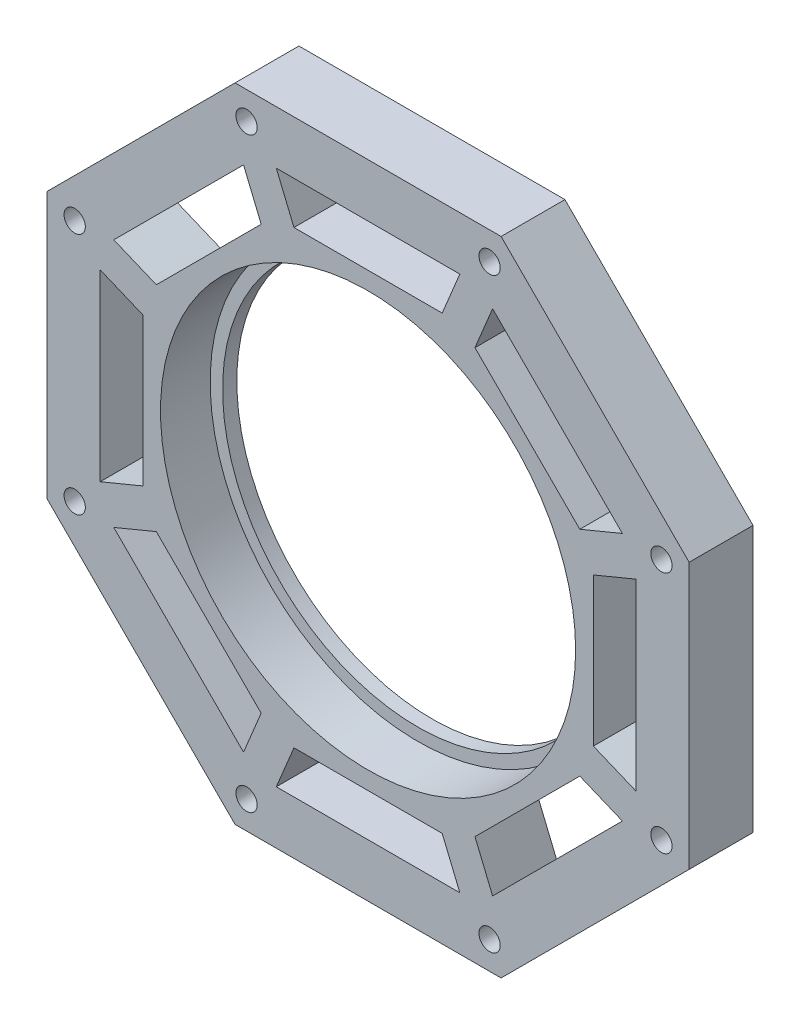
SolidWorks part; units mm, degrees
ref_plane "Front Plane" through (0, 0, 0) normal (0, 0, 1) x (1, 0, 0)
ref_plane "Top Plane" through (0, 0, 0) normal (0, 1, 0) x (1, 0, 0)
ref_plane "Right Plane" through (0, 0, 0) normal (1, 0, 0) x (0, 0, -1)
sketch "Sketch1" plane through (0, 0, 0) normal (0, 0, 1) x (1, 0, 0)
  line L0 (-45.25, -18.7432) -> (-45.25, 18.7432)
  line L1 (-45.25, 18.7432) -> (-18.7432, 45.25)
  line L2 (-18.7432, 45.25) -> (18.7432, 45.25)
  line L3 (18.7432, 45.25) -> (45.25, 18.7432)
  line L4 (45.25, 18.7432) -> (45.25, -18.7432)
  line L5 (45.25, -18.7432) -> (18.7432, -45.25)
  line L6 (18.7432, -45.25) -> (-18.7432, -45.25)
  line L7 (-18.7432, -45.25) -> (-45.25, -18.7432)
  circle A0 centre (0, 0) radius 27.5
  circle A1 centre (0, 0) radius 45.25 construction
  dimension "D1" = 90.5
  dimension "D3" = 55
  dimension "D2" = 135
extrude "Boss-Extrude1" add sketch "Sketch1" along normal blind 2
sketch "Sketch2" plane through (0, 0, 2) normal (0, 0, 1) x (1, 0, 0)
  line L0 (18.7432, 45.25) -> (-18.7432, 45.25) construction
  line L1 (45.25, 18.7432) -> (18.7432, 45.25) construction
  line L2 (45.25, -18.7432) -> (45.25, 18.7432) construction
  line L3 (18.7432, -45.25) -> (45.25, -18.7432) construction
  line L4 (-18.7432, -45.25) -> (18.7432, -45.25) construction
  line L5 (-45.25, -18.7432) -> (-18.7432, -45.25) construction
  line L6 (-45.25, 18.7432) -> (-45.25, -18.7432) construction
  line L7 (-18.7432, 45.25) -> (-45.25, 18.7432) construction
  line L8 (18.7432, 45.25) -> (-18.7432, 45.25)
  line L9 (45.25, 18.7432) -> (18.7432, 45.25)
  line L10 (45.25, -18.7432) -> (45.25, 18.7432)
  line L11 (18.7432, -45.25) -> (45.25, -18.7432)
  line L12 (-18.7432, -45.25) -> (18.7432, -45.25)
  line L13 (-45.25, -18.7432) -> (-18.7432, -45.25)
  line L14 (-45.25, 18.7432) -> (-45.25, -18.7432)
  line L15 (-18.7432, 45.25) -> (-45.25, 18.7432)
  circle A0 centre (0, 0) radius 29.25
  dimension "D1" = 58.5
extrude "Boss-Extrude2" add sketch "Sketch2" along normal blind 7
sketch "Sketch3" plane through (0, 0, 0) normal (0, 0, -1) x (-1, 0, 0)
  line L0 (0, 0) -> (18.7432, 45.25) construction
  circle A0 centre (0, 0) radius 45.25 construction
  circle A1 centre (0, 0) radius 45.25 construction
  circle A2 centre (0, 0) radius 44.75 construction
  circle A3 centre (17.1251, 41.3436) radius 1.5
  dimension "D2" = 3
  dimension "D1" = 0.5
extrude "Cut-Extrude1" cut sketch "Sketch3" against normal through all
pattern_circular "CirPattern1" count 8 over 360 about axis through (0, 0, 0) along (0, 0, 1) of "Cut-Extrude1"
sketch "Sketch6" plane through (0, 0, 9) normal (0, 0, 1) x (1, 0, 0)
  line L0 (0, 0) -> (-18.7432, 45.25) construction
  line L5 (0, 0) -> (18.7432, 45.25) construction
  line L6 (-13.1513, 31.75) -> (13.1513, 31.75) construction
  line L7 (15.6366, 37.75) -> (-15.6366, 37.75) construction
  line L10 (-10.4453, 31.75) -> (10.4453, 31.75)
  line L11 (18.7432, 45.25) -> (-18.7432, 45.25) construction
  line L12 (-12.9306, 37.75) -> (-10.4453, 31.75)
  line L13 (12.9306, 37.75) -> (10.4453, 31.75)
  line L14 (-12.9306, 37.75) -> (12.9306, 37.75)
  circle A0 centre (0, 0) radius 29.25 construction
  dimension "D1" = 31.75
  dimension "D2" = 7.5
  dimension "D3" = 2.5
  dimension "D4" = 2.5
extrude "Cut-Extrude2" cut sketch "Sketch6" against normal through all
pattern_circular "CirPattern2" count 8 over 360 about axis through (0, 0, 0) along (0, 0, 1) of "Cut-Extrude2"
